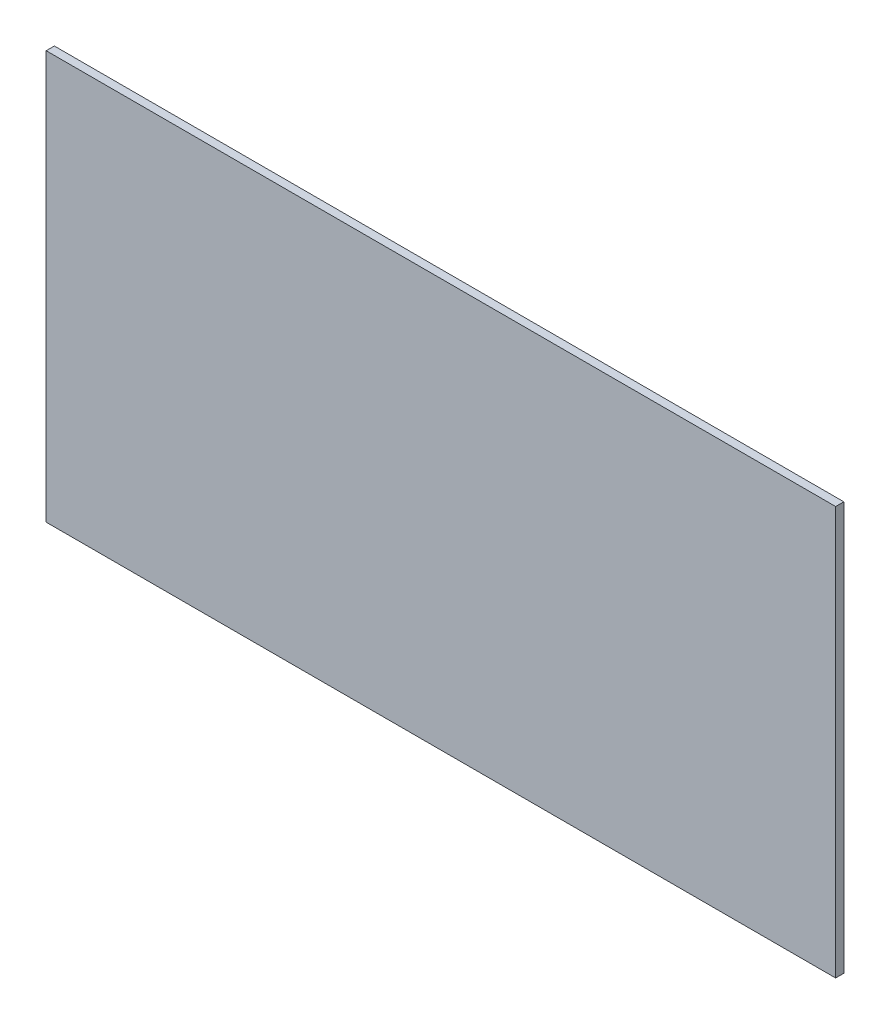
SolidWorks part; units mm, degrees
ref_plane "Front Plane" through (0, 0, 0) normal (0, 0, 1) x (1, 0, 0)
ref_plane "Top Plane" through (0, 0, 0) normal (0, 1, 0) x (1, 0, 0)
ref_plane "Right Plane" through (0, 0, 0) normal (1, 0, 0) x (0, 0, -1)
sketch "Sketch1" plane through (0, 0, 0) normal (0, 0, 1) x (1, 0, 0)
  line L1 (0, 0) -> (290, 0)
  line L2 (0, 0) -> (0, 150)
  line L3 (0, 150) -> (290, 150)
  line L4 (290, 0) -> (290, 150)
  dimension "D1" = 290
  dimension "D2" = 150
extrude "Boss-Extrude1" add sketch "Sketch1" along normal blind 3
